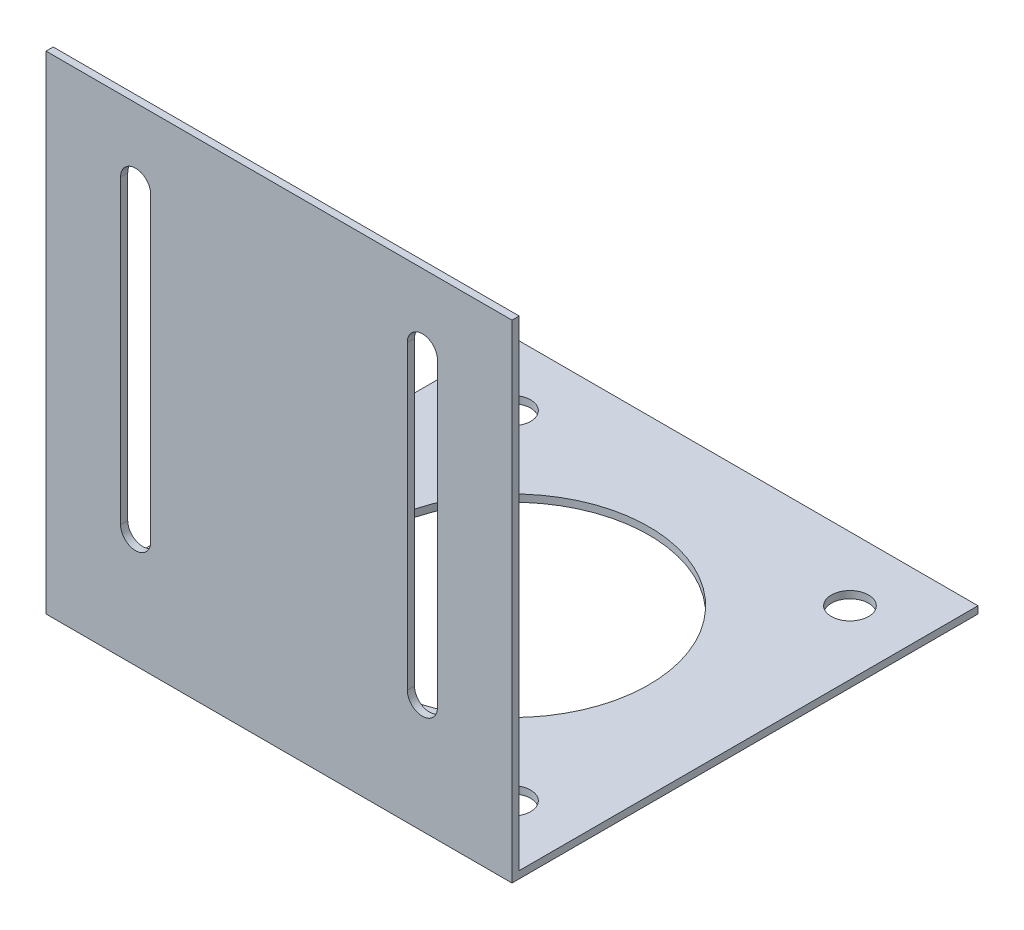
SolidWorks part; units mm, degrees
ref_plane "前视基准面" through (0, 0, 0) normal (0, 0, 1) x (1, 0, 0)
ref_plane "上视基准面" through (0, 0, 0) normal (0, 1, 0) x (1, 0, 0)
ref_plane "右视基准面" through (0, 0, 0) normal (1, 0, 0) x (0, 0, -1)
other "Configuration Table"
sketch "草图1" plane through (0, 0, 0) normal (0, 1, 0) x (1, 0, 0)
  line L0 (0, 32.5) -> (0, -32.5) construction
  line L1 (-32.5, 32.5) -> (32.5, 32.5)
  line L2 (-32.5, 32.5) -> (-32.5, -32.5)
  line L3 (-32.5, -32.5) -> (32.5, -32.5)
  line L4 (32.5, 32.5) -> (32.5, -32.5)
  line L5 (-32.5, 32.5) -> (32.5, -32.5) construction
  line L6 (-32.5, -32.5) -> (32.5, 32.5) construction
  line L7 (-32.5, 0) -> (32.5, 0) construction
  circle A0 centre (-23.57, 23.57) radius 2.6
  circle A1 centre (23.57, 23.57) radius 2.6
  circle A2 centre (23.57, -23.57) radius 2.6
  circle A3 centre (-23.57, -23.57) radius 2.6
  circle A4 centre (0, 0) radius 19.1
  point P0 (0, 0)
  dimension "D4" = 5.2
  dimension "D5" = 38.2
  dimension "D1" = 65
  dimension "D2" = 65
  dimension "D3" = 47.14
extrude "凸台-拉伸1" add sketch "草图1" along normal blind 1
sketch "草图2" plane through (0, 1, 0) normal (0, 1, 0) x (1, 0, 0)
  line L0 (32.5, -32.5) -> (32.5, 32.5) construction
  line L1 (-32.5, -32.5) -> (32.5, -32.5)
  line L2 (-32.5, -32.5) -> (-32.5, -31.5)
  line L3 (-32.5, -31.5) -> (32.5, -31.5)
  line L4 (32.5, -32.5) -> (32.5, -31.5)
  dimension "D1" = 1
extrude "凸台-拉伸2" add sketch "草图2" along normal blind 67
sketch "草图3" plane through (0, 0, 31.5) normal (0, 0, -1) x (-1, 0, 0)
  line L0 (-20, 58) -> (-20, 16) construction
  line L1 (-17.9, 58) -> (-17.9, 16)
  line L2 (-22.1, 58) -> (-22.1, 16)
  line L3 (-32.5, 68) -> (32.5, 68) construction
  line L4 (0, 68) -> (0, 1) construction
  line L5 (-32.5, 1) -> (32.5, 1) construction
  line L6 (20, 58) -> (20, 16) construction
  line L7 (17.9, 58) -> (17.9, 16)
  line L8 (22.1, 58) -> (22.1, 16)
  arc A0 (-17.9, 58) -> (-22.1, 58) centre (-20, 58) ccw
  arc A1 (-22.1, 16) -> (-17.9, 16) centre (-20, 16) ccw
  arc A2 (17.9, 58) -> (22.1, 58) centre (20, 58) cw
  arc A3 (22.1, 16) -> (17.9, 16) centre (20, 16) cw
  point P2 (-20, 37)
  point P15 (20, 37)
  dimension "D1" = 4.2
  dimension "D2" = 42
  dimension "D3" = 10
  dimension "D4" = 40
extrude "切除-拉伸1" cut sketch "草图3" against normal through all
